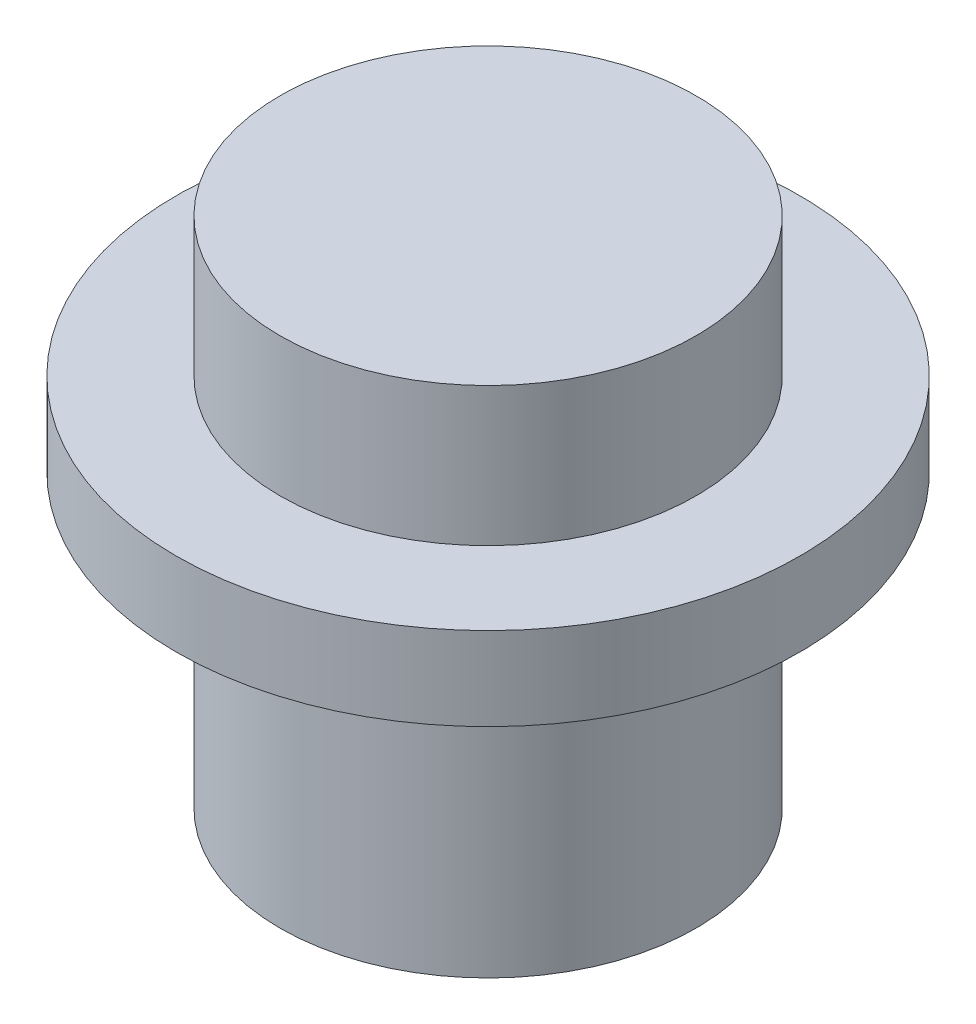
SolidWorks part; units mm, degrees
ref_plane "Спереди" through (0, 0, 0) normal (0, 0, 1) x (1, 0, 0)
ref_plane "Сверху" through (0, 0, 0) normal (0, 1, 0) x (1, 0, 0)
ref_plane "Справа" through (0, 0, 0) normal (1, 0, 0) x (0, 0, -1)
other "Configuration Table"
ref_plane "Плоскость1" through (0, -68, 0) normal (0, 1, 0) x (1, 0, 0)
sketch "Эскиз1" plane through (0, -68, 0) normal (0, 1, 0) x (1, 0, 0)
  circle A0 centre (38, -77) radius 3
extrude "Plunger_1" add sketch "Эскиз1" along normal blind 7.4
ref_plane "Плоскость2" through (0, -63.8, 0) normal (0, 1, 0) x (1, 0, 0)
sketch "Эскиз2" plane through (0, -63.8, 0) normal (0, 1, 0) x (1, 0, 0)
  circle A0 centre (38, -77) radius 4.5
extrude "Retention_flange_2" add sketch "Эскиз2" along normal blind 1.2
